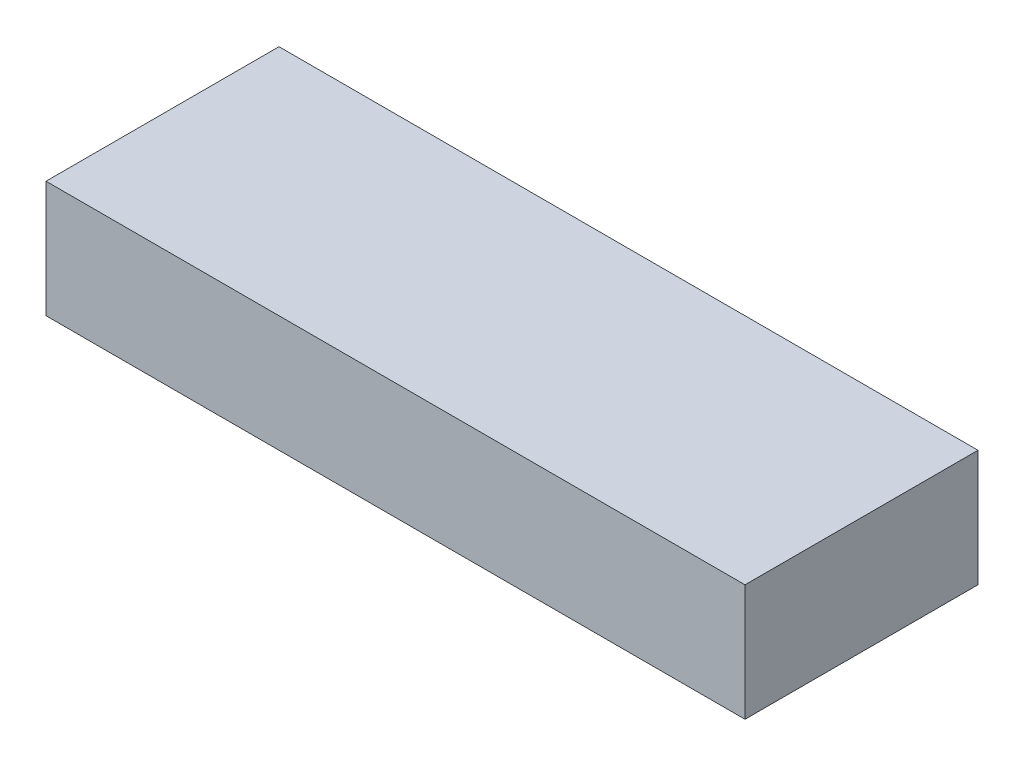
SolidWorks part; units mm, degrees
ref_plane "Front Plane" through (0, 0, 0) normal (0, 0, 1) x (1, 0, 0)
ref_plane "Top Plane" through (0, 0, 0) normal (0, 1, 0) x (1, 0, 0)
ref_plane "Right Plane" through (0, 0, 0) normal (1, 0, 0) x (0, 0, -1)
sketch "Sketch1" plane through (0, 0, 0) normal (0, 1, 0) x (1, 0, 0)
  line L1 (-152.4, -50.8) -> (152.4, -50.8)
  line L2 (-152.4, -50.8) -> (-152.4, 50.8)
  line L3 (-152.4, 50.8) -> (152.4, 50.8)
  line L4 (152.4, -50.8) -> (152.4, 50.8)
  line L5 (-152.4, -50.8) -> (152.4, 50.8) construction
  line L6 (-152.4, 50.8) -> (152.4, -50.8) construction
  point P0 (0, 0)
  dimension "D1" = 101.6
  dimension "D2" = 304.8
extrude "Boss-Extrude1" add sketch "Sketch1" along normal blind 50.8
